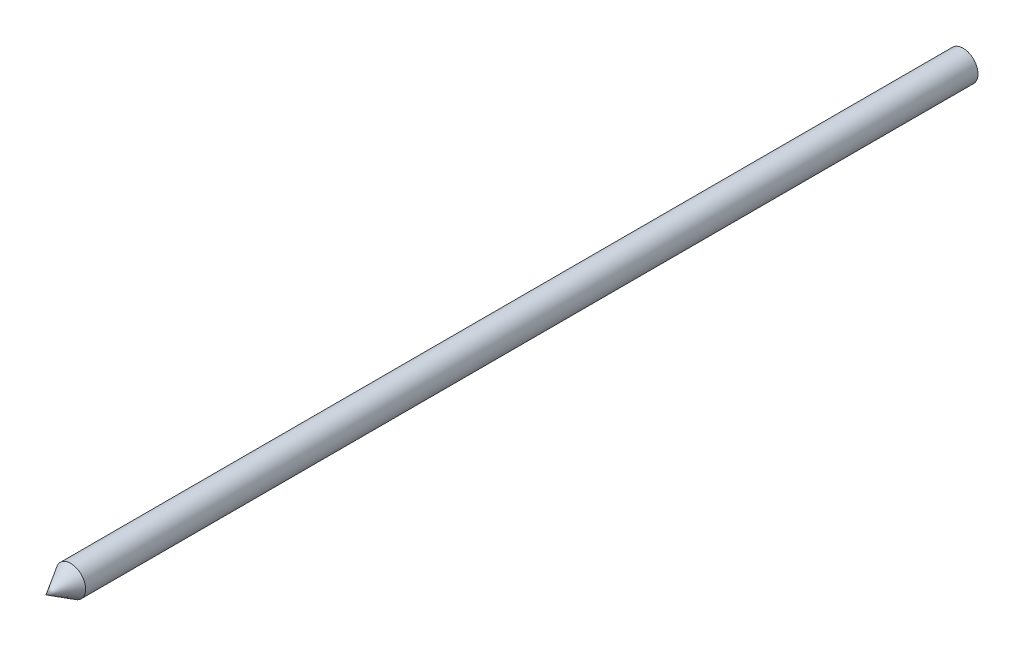
SolidWorks part; units mm, degrees
ref_plane "Plan de face" through (0, 0, 0) normal (0, 0, 1) x (1, 0, 0)
ref_plane "Plan de dessus" through (0, 0, 0) normal (0, 1, 0) x (1, 0, 0)
ref_plane "Plan de droite" through (0, 0, 0) normal (1, 0, 0) x (0, 0, -1)
sketch "Esquisse1" plane through (0, 0, 0) normal (0, 0, 1) x (1, 0, 0)
  circle A0 centre (0, 0) radius 15
extrude "Boss.-Extru.1" add sketch "Esquisse1" along normal blind 900
sketch "Esquisse2" plane through (0, 0, 900) normal (0, 0, 1) x (1, 0, 0)
  circle A0 centre (0, 0) radius 15
extrude "Boss.-Extru.2" add sketch "Esquisse2" along normal blind 30 draft 31
